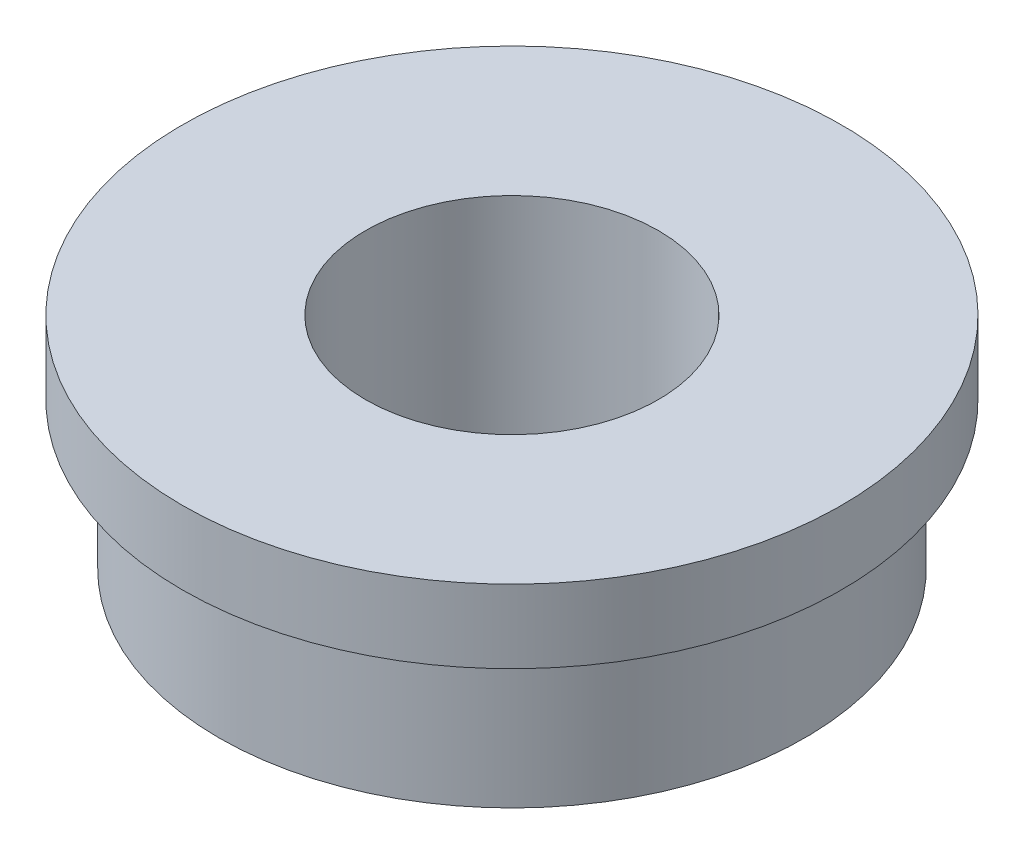
SolidWorks part; units mm, degrees
ref_plane "前视基准面" through (0, 0, 0) normal (0, 0, 1) x (1, 0, 0)
ref_plane "上视基准面" through (0, 0, 0) normal (0, 1, 0) x (1, 0, 0)
ref_plane "右视基准面" through (0, 0, 0) normal (1, 0, 0) x (0, 0, -1)
other "Configuration Table"
sketch "草图1" plane through (0, 0, 0) normal (0, 1, 0) x (1, 0, 0)
  circle A0 centre (0, 0) radius 4
  circle A1 centre (0, 0) radius 2
  dimension "D1" = 4
  dimension "D2" = 8
extrude "凸台-拉伸1" add sketch "草图1" along normal blind 2 contours A1 | A0
sketch "草图2" plane through (0, 2, 0) normal (0, 1, 0) x (1, 0, 0)
  circle A0 centre (0, 0) radius 4.5
  circle A1 centre (0, 0) radius 2 construction
  circle A2 centre (0, 0) radius 2
  dimension "D1" = 9
extrude "凸台-拉伸2" add sketch "草图2" along normal blind 1 contours A0 | A2
